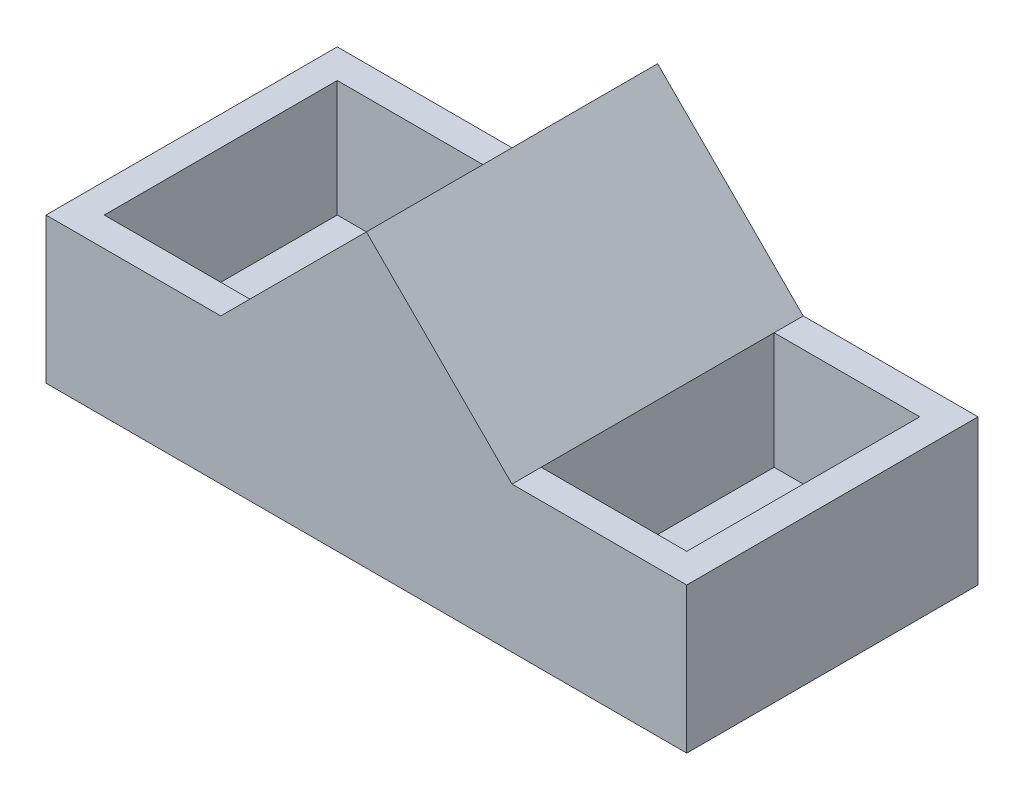
SolidWorks part; units mm, degrees
ref_plane "Front Plane" through (0, 0, 0) normal (0, 0, 1) x (1, 0, 0)
ref_plane "Top Plane" through (0, 0, 0) normal (0, 1, 0) x (1, 0, 0)
ref_plane "Right Plane" through (0, 0, 0) normal (1, 0, 0) x (0, 0, -1)
sketch "Sketch2" plane through (0, 0, 0) normal (0, 0, 1) x (1, 0, 0)
  line L0 (0, 0) -> (0, 100) construction
  line L1 (-50, 0) -> (50, 0)
  line L2 (-50, 0) -> (-50, 50)
  line L3 (-50, 50) -> (0, 100)
  line L4 (50, 0) -> (50, 50)
  line L5 (50, 50) -> (0, 100)
  point P6 (0, 0)
  dimension "D1" = 100
  dimension "D2" = 100
  dimension "D3" = 50
extrude "Boss-Extrude1" add sketch "Sketch2" along normal blind 100
sketch "Sketch4" plane through (50, 0, 0) normal (1, 0, 0) x (0, 0, -1)
  line L0 (-100, 50) -> (-100, 0)
  line L1 (-100, 0) -> (0, 0)
  line L2 (0, 0) -> (0, 50)
  line L3 (0, 0) -> (0, 50) construction
  line L4 (0, 50) -> (-10, 50)
  line L5 (-100, 50) -> (0, 50) construction
  line L7 (-10, 10) -> (-90, 10)
  line L8 (-90, 10) -> (-90, 50)
  line L9 (-90, 50) -> (-100, 50)
  line L10 (-10, 50) -> (-10, 10)
  dimension "D1" = 10
  dimension "D2" = 10
  dimension "D3" = 10
extrude "Boss-Extrude2" add sketch "Sketch4" along normal blind 50
sketch "Sketch5" plane through (100, 0, 0) normal (1, 0, 0) x (0, 0, -1)
  line L0 (-100, 0) -> (-100, 50)
  line L1 (-100, 50) -> (0, 50)
  line L2 (0, 50) -> (0, 0)
  line L3 (0, 0) -> (-100, 0)
extrude "Boss-Extrude3" add sketch "Sketch5" along normal blind 10
mirror "Mirror1" about plane through (0, 0, 0) normal (1, 0, 0) of "Boss-Extrude2", "Boss-Extrude3"
